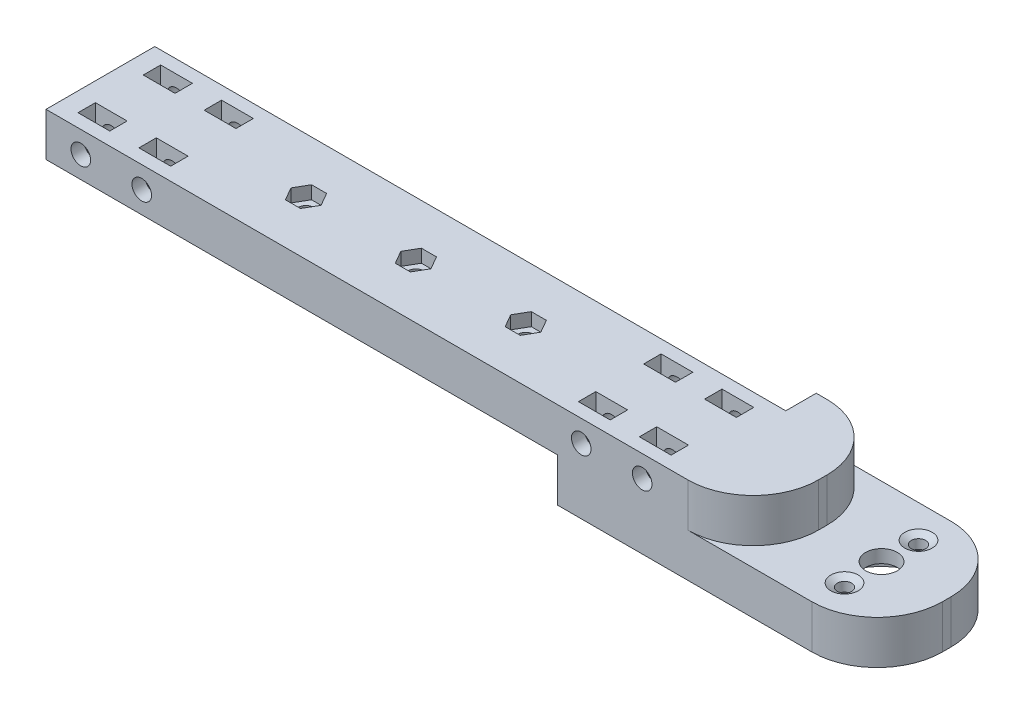
SolidWorks part; units mm, degrees
ref_plane "Front Plane" through (0, 0, 0) normal (0, 0, 1) x (1, 0, 0)
ref_plane "Top Plane" through (0, 0, 0) normal (0, 1, 0) x (1, 0, 0)
ref_plane "Right Plane" through (0, 0, 0) normal (1, 0, 0) x (0, 0, -1)
sketch "Sketch1" plane through (0, 0, 0) normal (0, 1, 0) x (1, 0, 0)
  line L7 (0, 0) -> (145, 0)
  line L8 (0, 0) -> (0, 25)
  line L9 (0, 25) -> (145, 25)
  line L10 (145, 0) -> (145, 25)
  dimension "D1" = 25
  dimension "D3" = 145
extrude "Boss-Extrude1" add sketch "Sketch1" along normal blind 10
sketch "Sketch2" plane through (0, 10, 0) normal (0, 1, 0) x (1, 0, 0)
  line L5 (145, 0) -> (162.5, 0)
  line L6 (145, 0) -> (145, 32)
  line L7 (145, 32) -> (162.5, 32)
  line L8 (162.5, 0) -> (162.5, 32)
  dimension "D1" = 17.5
  dimension "D2" = 32
extrude "Boss-Extrude2" add sketch "Sketch2" against normal blind 10
sketch "Sketch4" plane through (0, 0, 0) normal (0, -1, 0) x (1, 0, 0)
  line L0 (162.5, -32) -> (191, -32) construction
  line L1 (162.5, 0) -> (117.5, 0) construction
  line L2 (0, 0) -> (162.5, 0) construction
  line L4 (117.5, 0) -> (191, 0)
  line L5 (117.5, 0) -> (117.5, -32)
  line L6 (117.5, -32) -> (191, -32)
  line L7 (191, 0) -> (191, -32)
  dimension "D1" = 28.5
  dimension "D2" = 45
extrude "Boss-Extrude3" add sketch "Sketch4" along normal blind 10
sketch "Sketch8" plane through (0, 0, -25) normal (0, 0, -1) x (-1, 0, 0)
  line L0 (-145, 5) -> (0, 5) construction
  line L1 (-145, 10) -> (-145, 0) construction
  line L2 (0, 10) -> (0, 0) construction
  line L3 (-72.5, 10) -> (-72.5, 0) construction
  line L4 (0, 10) -> (-145, 10) construction
  line L5 (0, 0) -> (-117.5, 0) construction
  circle A0 centre (-137, 5) radius 2.25
  circle A1 centre (-123, 5) radius 2.25
  circle A2 centre (-22, 5) radius 2.25
  circle A3 centre (-8, 5) radius 2.25
  dimension "D1" = 8
  dimension "D2" = 4.5
  dimension "D4" = 14
  dimension "D3" = 2
extrude "Cut-Extrude5" cut sketch "Sketch8" against normal through all
sketch "Sketch9" plane through (0, 10, 0) normal (0, 1, 0) x (1, 0, 0)
  line L0 (145, 25) -> (145, 0) construction
  line L1 (0, 0) -> (162.5, 0) construction
  line L2 (145, 12.5) -> (0, 12.5) construction
  line L3 (0, 0) -> (0, 25) construction
  line L4 (72.5, 25) -> (72.5, 0) construction
  line L5 (0, 25) -> (145, 25) construction
  line L6 (137, 0) -> (137, 25) construction
  line L7 (140.65, 22) -> (133.35, 22)
  line L8 (140.65, 7) -> (133.35, 7)
  line L9 (140.65, 7) -> (140.65, 3)
  line L10 (140.65, 3) -> (133.35, 3)
  line L11 (133.35, 7) -> (133.35, 3)
  line L12 (140.65, 7) -> (133.35, 3) construction
  line L13 (140.65, 3) -> (133.35, 7) construction
  line L14 (133.35, 18) -> (133.35, 22)
  line L15 (140.65, 18) -> (133.35, 18)
  line L16 (140.65, 18) -> (140.65, 22)
  line L17 (126.65, 7) -> (126.65, 3)
  line L18 (126.65, 7) -> (119.35, 7)
  line L19 (119.35, 7) -> (119.35, 3)
  line L20 (126.65, 3) -> (119.35, 3)
  line L21 (126.65, 22) -> (119.35, 22)
  line L22 (119.35, 18) -> (119.35, 22)
  line L23 (126.65, 18) -> (119.35, 18)
  line L24 (126.65, 18) -> (126.65, 22)
  line L25 (4.35, 18) -> (4.35, 22)
  line L26 (4.35, 18) -> (11.65, 18)
  line L27 (11.65, 18) -> (11.65, 22)
  line L28 (4.35, 22) -> (11.65, 22)
  line L29 (18.35, 18) -> (18.35, 22)
  line L30 (18.35, 18) -> (25.65, 18)
  line L31 (25.65, 18) -> (25.65, 22)
  line L32 (18.35, 22) -> (25.65, 22)
  line L33 (18.35, 7) -> (25.65, 7)
  line L34 (25.65, 7) -> (25.65, 3)
  line L35 (18.35, 3) -> (25.65, 3)
  line L36 (18.35, 7) -> (18.35, 3)
  line L37 (4.35, 3) -> (11.65, 3)
  line L38 (11.65, 7) -> (11.65, 3)
  line L39 (4.35, 7) -> (11.65, 7)
  line L40 (4.35, 7) -> (4.35, 3)
  point P15 (137, 5)
  dimension "D1" = 8
  dimension "D2" = 5
  dimension "D3" = 7.3
  dimension "D4" = 4
  dimension "D6" = 14
  dimension "D5" = 2
extrude "Cut-Extrude6" cut sketch "Sketch9" against normal up to surface (10 mm away) up to face at (58.75, 0, -12.5)
sketch "Sketch10" plane through (0, 0, 0) normal (0, 1, 0) x (1, 0, 0)
  line L0 (191, 16) -> (162.5, 16) construction
  line L1 (191, 32) -> (191, 0) construction
  line L2 (162.5, 0) -> (162.5, 32) construction
  circle A0 centre (176, 16) radius 3.65
  dimension "D1" = 15
  dimension "D2" = 7.3
extrude "Cut-Extrude7" cut sketch "Sketch10" against normal up to next
sketch "Sketch11" plane through (0, -10, 0) normal (0, -1, 0) x (1, 0, 0)
  circle A0 centre (176, -16) radius 12.75
  dimension "D1" = 25.5
extrude "Cut-Extrude8" cut sketch "Sketch11" against normal blind 7
sketch "Sketch12" plane through (0, 10, 0) normal (0, 1, 0) x (1, 0, 0)
  line L0 (22, 22) -> (22, 3) construction
  line L1 (25.65, 22) -> (18.35, 22) construction
  line L2 (18.35, 3) -> (25.65, 3) construction
  line L3 (123, 22) -> (123, 3) construction
  line L4 (126.65, 22) -> (119.35, 22) construction
  line L5 (119.35, 3) -> (126.65, 3) construction
  line L6 (22, 12.5) -> (123, 12.5) construction
  line L7 (0, 0) -> (162.5, 0) construction
  circle A0 centre (72.5, 12.5) radius 1.75
  circle A1 centre (97.75, 12.5) radius 1.75
  circle A2 centre (72.5, 12.5) radius 1.75
  circle A3 centre (47.25, 12.5) radius 1.75
  dimension "D1" = 3.5
  dimension "D4" = 25.25
  dimension "D5" = 25.25
  dimension "D6" = 12.5
  dimension "D2" = 2
  dimension "D3" = 2
extrude "Cut-Extrude9" cut sketch "Sketch12" against normal up to next contours A3 | A0 | A1
sketch "Sketch13" plane through (0, 10, 0) normal (0, 1, 0) x (1, 0, 0)
  line L0 (75.9641, 12.5) -> (74.2321, 15.5)
  line L1 (50.7141, 12.5) -> (48.9821, 15.5)
  line L2 (48.9821, 15.5) -> (45.5179, 15.5)
  line L3 (45.5179, 15.5) -> (43.7859, 12.5)
  line L4 (43.7859, 12.5) -> (45.5179, 9.5)
  line L5 (45.5179, 9.5) -> (48.9821, 9.5)
  line L6 (48.9821, 9.5) -> (50.7141, 12.5)
  line L7 (74.2321, 15.5) -> (70.7679, 15.5)
  line L8 (70.7679, 15.5) -> (69.0359, 12.5)
  line L9 (69.0359, 12.5) -> (70.7679, 9.5)
  line L10 (70.7679, 9.5) -> (74.2321, 9.5)
  line L11 (74.2321, 9.5) -> (75.9641, 12.5)
  line L12 (101.2141, 12.5) -> (99.4821, 15.5)
  line L13 (99.4821, 15.5) -> (96.0179, 15.5)
  line L14 (96.0179, 15.5) -> (94.2859, 12.5)
  line L15 (94.2859, 12.5) -> (96.0179, 9.5)
  line L16 (96.0179, 9.5) -> (99.4821, 9.5)
  line L17 (99.4821, 9.5) -> (101.2141, 12.5)
  circle A0 centre (47.25, 12.5) radius 3 construction
  dimension "D1" = 6
  dimension "D4" = 25.25
  dimension "D2" = 3
  dimension "D3" = 3
extrude "Cut-Extrude10" cut sketch "Sketch13" against normal blind 3
sketch "Sketch14" plane through (0, -3, 0) normal (0, -1, 0) x (1, 0, 0)
  line L0 (176, -16) -> (176, -3.25) construction
  line L1 (163.25, -16) -> (188.75, -16) construction
  circle A0 centre (176, -16) radius 12.75 construction
  circle A1 centre (176, -7.5) radius 1.65
  circle A2 centre (176, -16) radius 12.75 construction
  circle A3 centre (176, -24.5) radius 1.65
  dimension "D1" = 3.3
  dimension "D2" = 8.5
extrude "Cut-Extrude11" cut sketch "Sketch14" against normal up to next
chamfer "Chamfer1" distance 1.5 angle 30 2 edges at (176, 0, -26.15) (176, 0, -9.15)
fillet "Fillet1" radius 15 4 edges at (162.5, 5, 0) (162.5, 5, -32) (191, -5, -32) (191, -5, 0)
